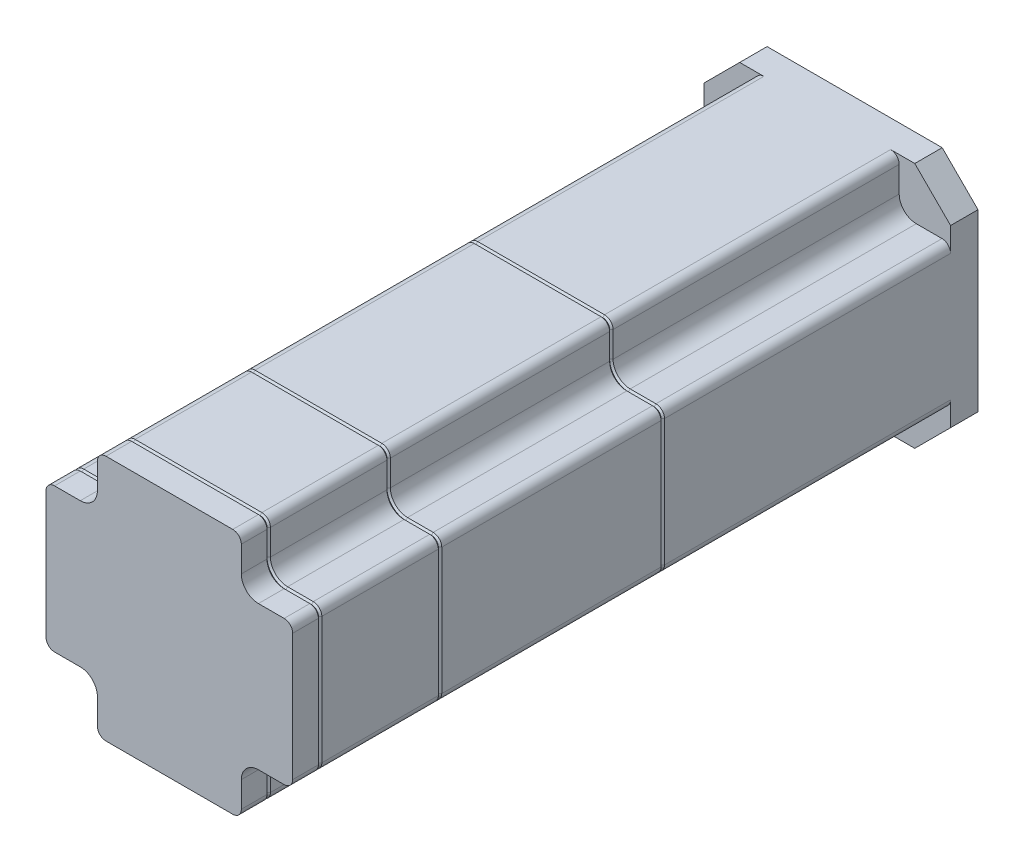
SolidWorks part; units mm, degrees
ref_plane "Front Plane" through (0, 0, 0) normal (0, 0, 1) x (1, 0, 0)
ref_plane "Top Plane" through (0, 0, 0) normal (0, 1, 0) x (1, 0, 0)
ref_plane "Right Plane" through (0, 0, 0) normal (1, 0, 0) x (0, 0, -1)
sketch "Sketch3" plane through (0, 0, 0) normal (0, 0, 1) x (1, 0, 0)
  line L1 (-36, -36) -> (36, -36)
  line L2 (-36, -36) -> (-36, 36)
  line L3 (-36, 36) -> (36, 36)
  line L4 (36, -36) -> (36, 36)
  line L5 (-36, -36) -> (36, 36) construction
  line L6 (-36, 36) -> (36, -36) construction
  point P0 (0, 0)
  dimension "D1" = 72
  dimension "D2" = 72
extrude "Boss-Extrude2" add sketch "Sketch3" along normal blind 8
chamfer "Chamfer1" distance 10.45 angle 45 4 edges at (36, -36, 4) (-36, -36, 4) (-36, 36, 4) (36, 36, 4)
sketch "Sketch5" plane through (0, 0, 8) normal (0, 0, 1) x (1, 0, 0)
  line L3 (-36, -21) -> (-26, -21)
  line L4 (-21, -36) -> (-21, -26)
  line L5 (-36, -36) -> (-21, -21) construction
  line L6 (-36, -21) -> (-21, -36) construction
  line L8 (-21, 36) -> (-21, 26)
  line L9 (-36, 21) -> (-26, 21)
  line L10 (36, 21) -> (26, 21)
  line L11 (21, 36) -> (21, 26)
  line L12 (21, -36) -> (21, -26)
  line L13 (36, -21) -> (26, -21)
  line L20 (-25.55, -36) -> (25.55, -36)
  line L21 (25.55, -36) -> (36, -25.55)
  line L22 (36, -25.55) -> (36, 25.55)
  line L23 (36, 25.55) -> (25.55, 36)
  line L24 (25.55, 36) -> (-25.55, 36)
  line L25 (-25.55, 36) -> (-36, 25.55)
  line L26 (-36, 25.55) -> (-36, -25.55)
  line L27 (-36, -25.55) -> (-25.55, -36)
  line L28 (-25.55, -36) -> (25.55, -36)
  line L29 (25.55, -36) -> (36, -25.55)
  line L30 (36, -25.55) -> (36, 25.55)
  line L31 (36, 25.55) -> (25.55, 36)
  line L32 (25.55, 36) -> (-25.55, 36)
  line L33 (-25.55, 36) -> (-36, 25.55)
  line L34 (-36, 25.55) -> (-36, -25.55)
  line L35 (-36, -25.55) -> (-25.55, -36)
  arc A0 (-26, -21) -> (-21, -26) centre (-26, -26) cw
  arc A1 (-21, 26) -> (-26, 21) centre (-26, 26) cw
  arc A2 (26, 21) -> (21, 26) centre (26, 26) cw
  arc A3 (21, -26) -> (26, -21) centre (26, -26) cw
  point P0 (-28.5, -28.5)
  point P30 (0, 0)
  line M12 (-25.55, -36) -> (25.55, -36)
  line M14 (36, -25.55) -> (36, 25.55)
  line M16 (25.55, 36) -> (-25.55, 36)
  line M18 (-36, 25.55) -> (-36, -25.55)
  dimension "D5" = 5
  dimension "D1" = 0
  dimension "D3" = 15
  dimension "D6" = 4
extrude "Boss-Extrude3" add sketch "Sketch5" along normal blind 192 contours L12 A3 L13 L10 A2 L11 L8 A1 L9 L3 A0 L4 M14 M16 M18 M12
fillet "Fillet1" radius 2.5 8 edges at (-36, -21, 104) (-21, -36, 104) (21, -36, 104) (36, -21, 104) (36, 21, 104) (21, 36, 104) (-21, 36, 104) (-36, 21, 104)
ref_plane "Plane1" through (0, 0, 192) normal (0, 0, 1) x (1, 0, 0)
sketch "Sketch8" plane through (0, 0, 192) normal (0, 0, 1) x (1, 0, 0)
  line L24 (-46, 18.5) -> (-46, -18.5)
  line L25 (-33.5, -31) -> (-31, -31)
  line L26 (-31, -31) -> (-31, -33.5)
  line L27 (-18.5, -46) -> (18.5, -46)
  line L28 (31, -33.5) -> (31, -31)
  line L29 (31, -31) -> (33.5, -31)
  line L30 (46, -18.5) -> (46, 18.5)
  line L31 (33.5, 31) -> (31, 31)
  line L32 (31, 31) -> (31, 33.5)
  line L33 (18.5, 46) -> (-18.5, 46)
  line L34 (-31, 33.5) -> (-31, 31)
  line L35 (-31, 31) -> (-33.5, 31)
  line L36 (-46, 18.5) -> (-46, -18.5)
  line L37 (-33.5, -31) -> (-31, -31)
  line L38 (-31, -31) -> (-31, -33.5)
  line L39 (-18.5, -46) -> (18.5, -46)
  line L40 (31, -33.5) -> (31, -31)
  line L41 (31, -31) -> (33.5, -31)
  line L42 (46, -18.5) -> (46, 18.5)
  line L43 (33.5, 31) -> (31, 31)
  line L44 (31, 31) -> (31, 33.5)
  line L45 (18.5, 46) -> (-18.5, 46)
  line L46 (-31, 33.5) -> (-31, 31)
  line L47 (-31, 31) -> (-33.5, 31)
  line L60 (-35.5, 18.5) -> (-35.5, -18.5)
  line L61 (-33.5, -20.5) -> (-26, -20.5)
  line L62 (-20.5, -26) -> (-20.5, -33.5)
  line L63 (-18.5, -35.5) -> (18.5, -35.5)
  line L64 (20.5, -33.5) -> (20.5, -26)
  line L65 (26, -20.5) -> (33.5, -20.5)
  line L66 (35.5, -18.5) -> (35.5, 18.5)
  line L67 (33.5, 20.5) -> (26, 20.5)
  line L68 (20.5, 26) -> (20.5, 33.5)
  line L69 (18.5, 35.5) -> (-18.5, 35.5)
  line L70 (-20.5, 33.5) -> (-20.5, 26)
  line L71 (-26, 20.5) -> (-33.5, 20.5)
  line L72 (-35.5, 18.5) -> (-35.5, -18.5)
  line L73 (-33.5, -20.5) -> (-26, -20.5)
  line L74 (-20.5, -26) -> (-20.5, -33.5)
  line L75 (-18.5, -35.5) -> (18.5, -35.5)
  line L76 (20.5, -33.5) -> (20.5, -26)
  line L77 (26, -20.5) -> (33.5, -20.5)
  line L78 (35.5, -18.5) -> (35.5, 18.5)
  line L79 (33.5, 20.5) -> (26, 20.5)
  line L80 (20.5, 26) -> (20.5, 33.5)
  line L81 (18.5, 35.5) -> (-18.5, 35.5)
  line L82 (-20.5, 33.5) -> (-20.5, 26)
  line L83 (-26, 20.5) -> (-33.5, 20.5)
  arc A24 (-46, -18.5) -> (-33.5, -31) centre (-33.5, -18.5) ccw
  arc A25 (-31, -33.5) -> (-18.5, -46) centre (-18.5, -33.5) ccw
  arc A26 (18.5, -46) -> (31, -33.5) centre (18.5, -33.5) ccw
  arc A27 (33.5, -31) -> (46, -18.5) centre (33.5, -18.5) ccw
  arc A28 (46, 18.5) -> (33.5, 31) centre (33.5, 18.5) ccw
  arc A29 (31, 33.5) -> (18.5, 46) centre (18.5, 33.5) ccw
  arc A30 (-18.5, 46) -> (-31, 33.5) centre (-18.5, 33.5) ccw
  arc A31 (-33.5, 31) -> (-46, 18.5) centre (-33.5, 18.5) ccw
  arc A32 (-46, -18.5) -> (-33.5, -31) centre (-33.5, -18.5) ccw
  arc A33 (-31, -33.5) -> (-18.5, -46) centre (-18.5, -33.5) ccw
  arc A34 (18.5, -46) -> (31, -33.5) centre (18.5, -33.5) ccw
  arc A35 (33.5, -31) -> (46, -18.5) centre (33.5, -18.5) ccw
  arc A36 (46, 18.5) -> (33.5, 31) centre (33.5, 18.5) ccw
  arc A37 (31, 33.5) -> (18.5, 46) centre (18.5, 33.5) ccw
  arc A38 (-18.5, 46) -> (-31, 33.5) centre (-18.5, 33.5) ccw
  arc A39 (-33.5, 31) -> (-46, 18.5) centre (-33.5, 18.5) ccw
  arc A52 (-35.5, -18.5) -> (-33.5, -20.5) centre (-33.5, -18.5) ccw
  arc A53 (-20.5, -26) -> (-26, -20.5) centre (-26, -26) ccw
  arc A54 (-20.5, -33.5) -> (-18.5, -35.5) centre (-18.5, -33.5) ccw
  arc A55 (18.5, -35.5) -> (20.5, -33.5) centre (18.5, -33.5) ccw
  arc A56 (26, -20.5) -> (20.5, -26) centre (26, -26) ccw
  arc A57 (33.5, -20.5) -> (35.5, -18.5) centre (33.5, -18.5) ccw
  arc A58 (35.5, 18.5) -> (33.5, 20.5) centre (33.5, 18.5) ccw
  arc A59 (20.5, 26) -> (26, 20.5) centre (26, 26) ccw
  arc A60 (20.5, 33.5) -> (18.5, 35.5) centre (18.5, 33.5) ccw
  arc A61 (-18.5, 35.5) -> (-20.5, 33.5) centre (-18.5, 33.5) ccw
  arc A62 (-26, 20.5) -> (-20.5, 26) centre (-26, 26) ccw
  arc A63 (-33.5, 20.5) -> (-35.5, 18.5) centre (-33.5, 18.5) ccw
  arc A64 (-35.5, -18.5) -> (-33.5, -20.5) centre (-33.5, -18.5) ccw
  arc A65 (-20.5, -26) -> (-26, -20.5) centre (-26, -26) ccw
  arc A66 (-20.5, -33.5) -> (-18.5, -35.5) centre (-18.5, -33.5) ccw
  arc A67 (18.5, -35.5) -> (20.5, -33.5) centre (18.5, -33.5) ccw
  arc A68 (26, -20.5) -> (20.5, -26) centre (26, -26) ccw
  arc A69 (33.5, -20.5) -> (35.5, -18.5) centre (33.5, -18.5) ccw
  arc A70 (35.5, 18.5) -> (33.5, 20.5) centre (33.5, 18.5) ccw
  arc A71 (20.5, 26) -> (26, 20.5) centre (26, 26) ccw
  arc A72 (20.5, 33.5) -> (18.5, 35.5) centre (18.5, 33.5) ccw
  arc A73 (-18.5, 35.5) -> (-20.5, 33.5) centre (-18.5, 33.5) ccw
  arc A74 (-26, 20.5) -> (-20.5, 26) centre (-26, 26) ccw
  arc A75 (-33.5, 20.5) -> (-35.5, 18.5) centre (-33.5, 18.5) ccw
  dimension "D1" = 10
  dimension "D2" = 0.5
extrude "Cut-Extrude2" cut sketch "Sketch8" against normal blind 0.5 draft 45 and the other way blind 0.5 draft 45
ref_plane "Plane2" through (0, 0, 157) normal (0, 0, 1) x (1, 0, 0)
sketch "Sketch9" plane through (0, 0, 157) normal (0, 0, 1) x (1, 0, 0)
  line L12 (31, -31) -> (33.5, -31)
  line L13 (31, -33.5) -> (31, -31)
  line L14 (-18.5, -46) -> (18.5, -46)
  line L15 (-31, -31) -> (-31, -33.5)
  line L16 (-33.5, -31) -> (-31, -31)
  line L17 (-46, 18.5) -> (-46, -18.5)
  line L18 (-31, 31) -> (-33.5, 31)
  line L19 (-31, 33.5) -> (-31, 31)
  line L20 (18.5, 46) -> (-18.5, 46)
  line L21 (31, 31) -> (31, 33.5)
  line L22 (33.5, 31) -> (31, 31)
  line L23 (46, -18.5) -> (46, 18.5)
  line L24 (31, -31) -> (33.5, -31)
  line L25 (31, -33.5) -> (31, -31)
  line L26 (-18.5, -46) -> (18.5, -46)
  line L27 (-31, -31) -> (-31, -33.5)
  line L28 (-33.5, -31) -> (-31, -31)
  line L29 (-46, 18.5) -> (-46, -18.5)
  line L30 (-31, 31) -> (-33.5, 31)
  line L31 (-31, 33.5) -> (-31, 31)
  line L32 (18.5, 46) -> (-18.5, 46)
  line L33 (31, 31) -> (31, 33.5)
  line L34 (33.5, 31) -> (31, 31)
  line L35 (46, -18.5) -> (46, 18.5)
  line L36 (20.5, 26) -> (20.5, 33.5)
  line L37 (18.5, 35.5) -> (-18.5, 35.5)
  line L38 (-20.5, 33.5) -> (-20.5, 26)
  line L39 (-26, 20.5) -> (-33.5, 20.5)
  line L40 (-35.5, 18.5) -> (-35.5, -18.5)
  line L41 (-33.5, -20.5) -> (-26, -20.5)
  line L42 (-20.5, -26) -> (-20.5, -33.5)
  line L43 (-18.5, -35.5) -> (18.5, -35.5)
  line L44 (20.5, -33.5) -> (20.5, -26)
  line L45 (26, -20.5) -> (33.5, -20.5)
  line L46 (35.5, -18.5) -> (35.5, 18.5)
  line L47 (33.5, 20.5) -> (26, 20.5)
  line L48 (20.5, 26) -> (20.5, 33.5)
  line L49 (18.5, 35.5) -> (-18.5, 35.5)
  line L50 (-20.5, 33.5) -> (-20.5, 26)
  line L51 (-26, 20.5) -> (-33.5, 20.5)
  line L52 (-35.5, 18.5) -> (-35.5, -18.5)
  line L53 (-33.5, -20.5) -> (-26, -20.5)
  line L54 (-20.5, -26) -> (-20.5, -33.5)
  line L55 (-18.5, -35.5) -> (18.5, -35.5)
  line L56 (20.5, -33.5) -> (20.5, -26)
  line L57 (26, -20.5) -> (33.5, -20.5)
  line L58 (35.5, -18.5) -> (35.5, 18.5)
  line L59 (33.5, 20.5) -> (26, 20.5)
  arc A8 (18.5, -46) -> (31, -33.5) centre (18.5, -33.5) ccw
  arc A9 (-31, -33.5) -> (-18.5, -46) centre (-18.5, -33.5) ccw
  arc A10 (-46, -18.5) -> (-33.5, -31) centre (-33.5, -18.5) ccw
  arc A11 (-33.5, 31) -> (-46, 18.5) centre (-33.5, 18.5) ccw
  arc A12 (-18.5, 46) -> (-31, 33.5) centre (-18.5, 33.5) ccw
  arc A13 (31, 33.5) -> (18.5, 46) centre (18.5, 33.5) ccw
  arc A14 (46, 18.5) -> (33.5, 31) centre (33.5, 18.5) ccw
  arc A15 (33.5, -31) -> (46, -18.5) centre (33.5, -18.5) ccw
  arc A16 (18.5, -46) -> (31, -33.5) centre (18.5, -33.5) ccw
  arc A17 (-31, -33.5) -> (-18.5, -46) centre (-18.5, -33.5) ccw
  arc A18 (-46, -18.5) -> (-33.5, -31) centre (-33.5, -18.5) ccw
  arc A19 (-33.5, 31) -> (-46, 18.5) centre (-33.5, 18.5) ccw
  arc A20 (-18.5, 46) -> (-31, 33.5) centre (-18.5, 33.5) ccw
  arc A21 (31, 33.5) -> (18.5, 46) centre (18.5, 33.5) ccw
  arc A22 (46, 18.5) -> (33.5, 31) centre (33.5, 18.5) ccw
  arc A23 (33.5, -31) -> (46, -18.5) centre (33.5, -18.5) ccw
  arc A28 (20.5, 33.5) -> (18.5, 35.5) centre (18.5, 33.5) ccw
  arc A29 (-18.5, 35.5) -> (-20.5, 33.5) centre (-18.5, 33.5) ccw
  arc A30 (-26, 20.5) -> (-20.5, 26) centre (-26, 26) ccw
  arc A31 (-33.5, 20.5) -> (-35.5, 18.5) centre (-33.5, 18.5) ccw
  arc A32 (-35.5, -18.5) -> (-33.5, -20.5) centre (-33.5, -18.5) ccw
  arc A33 (-20.5, -26) -> (-26, -20.5) centre (-26, -26) ccw
  arc A34 (-20.5, -33.5) -> (-18.5, -35.5) centre (-18.5, -33.5) ccw
  arc A35 (18.5, -35.5) -> (20.5, -33.5) centre (18.5, -33.5) ccw
  arc A36 (26, -20.5) -> (20.5, -26) centre (26, -26) ccw
  arc A37 (33.5, -20.5) -> (35.5, -18.5) centre (33.5, -18.5) ccw
  arc A38 (35.5, 18.5) -> (33.5, 20.5) centre (33.5, 18.5) ccw
  arc A39 (20.5, 26) -> (26, 20.5) centre (26, 26) ccw
  arc A40 (20.5, 33.5) -> (18.5, 35.5) centre (18.5, 33.5) ccw
  arc A41 (-18.5, 35.5) -> (-20.5, 33.5) centre (-18.5, 33.5) ccw
  arc A42 (-26, 20.5) -> (-20.5, 26) centre (-26, 26) ccw
  arc A43 (-33.5, 20.5) -> (-35.5, 18.5) centre (-33.5, 18.5) ccw
  arc A44 (-35.5, -18.5) -> (-33.5, -20.5) centre (-33.5, -18.5) ccw
  arc A45 (-20.5, -26) -> (-26, -20.5) centre (-26, -26) ccw
  arc A46 (-20.5, -33.5) -> (-18.5, -35.5) centre (-18.5, -33.5) ccw
  arc A47 (18.5, -35.5) -> (20.5, -33.5) centre (18.5, -33.5) ccw
  arc A48 (26, -20.5) -> (20.5, -26) centre (26, -26) ccw
  arc A49 (33.5, -20.5) -> (35.5, -18.5) centre (33.5, -18.5) ccw
  arc A50 (35.5, 18.5) -> (33.5, 20.5) centre (33.5, 18.5) ccw
  arc A51 (20.5, 26) -> (26, 20.5) centre (26, 26) ccw
  dimension "D1" = 0
  dimension "D2" = 0
extrude "Cut-Extrude3" cut sketch "Sketch9" against normal blind 0.5 draft 45 and the other way blind 0.5 draft 45
ref_plane "Plane3" through (0, 0, 92) normal (0, 0, 1) x (1, 0, 0)
sketch "Sketch10" plane through (0, 0, 92) normal (0, 0, 1) x (1, 0, 0)
  line L12 (18.5, 46) -> (-18.5, 46)
  line L13 (31, 31) -> (31, 33.5)
  line L14 (33.5, 31) -> (31, 31)
  line L15 (46, -18.5) -> (46, 18.5)
  line L16 (31, -31) -> (33.5, -31)
  line L17 (31, -33.5) -> (31, -31)
  line L18 (-18.5, -46) -> (18.5, -46)
  line L19 (-31, -31) -> (-31, -33.5)
  line L20 (-33.5, -31) -> (-31, -31)
  line L21 (-46, 18.5) -> (-46, -18.5)
  line L22 (-31, 31) -> (-33.5, 31)
  line L23 (-31, 33.5) -> (-31, 31)
  line L24 (18.5, 46) -> (-18.5, 46)
  line L25 (31, 31) -> (31, 33.5)
  line L26 (33.5, 31) -> (31, 31)
  line L27 (46, -18.5) -> (46, 18.5)
  line L28 (31, -31) -> (33.5, -31)
  line L29 (31, -33.5) -> (31, -31)
  line L30 (-18.5, -46) -> (18.5, -46)
  line L31 (-31, -31) -> (-31, -33.5)
  line L32 (-33.5, -31) -> (-31, -31)
  line L33 (-46, 18.5) -> (-46, -18.5)
  line L34 (-31, 31) -> (-33.5, 31)
  line L35 (-31, 33.5) -> (-31, 31)
  line L36 (-18.5, -35.5) -> (18.5, -35.5)
  line L37 (-20.5, -26) -> (-20.5, -33.5)
  line L38 (-33.5, -20.5) -> (-26, -20.5)
  line L39 (-35.5, 18.5) -> (-35.5, -18.5)
  line L40 (-26, 20.5) -> (-33.5, 20.5)
  line L41 (-20.5, 33.5) -> (-20.5, 26)
  line L42 (18.5, 35.5) -> (-18.5, 35.5)
  line L43 (20.5, 26) -> (20.5, 33.5)
  line L44 (33.5, 20.5) -> (26, 20.5)
  line L45 (35.5, -18.5) -> (35.5, 18.5)
  line L46 (26, -20.5) -> (33.5, -20.5)
  line L47 (20.5, -33.5) -> (20.5, -26)
  line L48 (-18.5, -35.5) -> (18.5, -35.5)
  line L49 (-20.5, -26) -> (-20.5, -33.5)
  line L50 (-33.5, -20.5) -> (-26, -20.5)
  line L51 (-35.5, 18.5) -> (-35.5, -18.5)
  line L52 (-26, 20.5) -> (-33.5, 20.5)
  line L53 (-20.5, 33.5) -> (-20.5, 26)
  line L54 (18.5, 35.5) -> (-18.5, 35.5)
  line L55 (20.5, 26) -> (20.5, 33.5)
  line L56 (33.5, 20.5) -> (26, 20.5)
  line L57 (35.5, -18.5) -> (35.5, 18.5)
  line L58 (26, -20.5) -> (33.5, -20.5)
  line L59 (20.5, -33.5) -> (20.5, -26)
  arc A8 (-18.5, 46) -> (-31, 33.5) centre (-18.5, 33.5) ccw
  arc A9 (31, 33.5) -> (18.5, 46) centre (18.5, 33.5) ccw
  arc A10 (46, 18.5) -> (33.5, 31) centre (33.5, 18.5) ccw
  arc A11 (33.5, -31) -> (46, -18.5) centre (33.5, -18.5) ccw
  arc A12 (18.5, -46) -> (31, -33.5) centre (18.5, -33.5) ccw
  arc A13 (-31, -33.5) -> (-18.5, -46) centre (-18.5, -33.5) ccw
  arc A14 (-46, -18.5) -> (-33.5, -31) centre (-33.5, -18.5) ccw
  arc A15 (-33.5, 31) -> (-46, 18.5) centre (-33.5, 18.5) ccw
  arc A16 (-18.5, 46) -> (-31, 33.5) centre (-18.5, 33.5) ccw
  arc A17 (31, 33.5) -> (18.5, 46) centre (18.5, 33.5) ccw
  arc A18 (46, 18.5) -> (33.5, 31) centre (33.5, 18.5) ccw
  arc A19 (33.5, -31) -> (46, -18.5) centre (33.5, -18.5) ccw
  arc A20 (18.5, -46) -> (31, -33.5) centre (18.5, -33.5) ccw
  arc A21 (-31, -33.5) -> (-18.5, -46) centre (-18.5, -33.5) ccw
  arc A22 (-46, -18.5) -> (-33.5, -31) centre (-33.5, -18.5) ccw
  arc A23 (-33.5, 31) -> (-46, 18.5) centre (-33.5, 18.5) ccw
  arc A28 (18.5, -35.5) -> (20.5, -33.5) centre (18.5, -33.5) ccw
  arc A29 (-20.5, -33.5) -> (-18.5, -35.5) centre (-18.5, -33.5) ccw
  arc A30 (-20.5, -26) -> (-26, -20.5) centre (-26, -26) ccw
  arc A31 (-35.5, -18.5) -> (-33.5, -20.5) centre (-33.5, -18.5) ccw
  arc A32 (-33.5, 20.5) -> (-35.5, 18.5) centre (-33.5, 18.5) ccw
  arc A33 (-26, 20.5) -> (-20.5, 26) centre (-26, 26) ccw
  arc A34 (-18.5, 35.5) -> (-20.5, 33.5) centre (-18.5, 33.5) ccw
  arc A35 (20.5, 33.5) -> (18.5, 35.5) centre (18.5, 33.5) ccw
  arc A36 (20.5, 26) -> (26, 20.5) centre (26, 26) ccw
  arc A37 (35.5, 18.5) -> (33.5, 20.5) centre (33.5, 18.5) ccw
  arc A38 (33.5, -20.5) -> (35.5, -18.5) centre (33.5, -18.5) ccw
  arc A39 (26, -20.5) -> (20.5, -26) centre (26, -26) ccw
  arc A40 (18.5, -35.5) -> (20.5, -33.5) centre (18.5, -33.5) ccw
  arc A41 (-20.5, -33.5) -> (-18.5, -35.5) centre (-18.5, -33.5) ccw
  arc A42 (-20.5, -26) -> (-26, -20.5) centre (-26, -26) ccw
  arc A43 (-35.5, -18.5) -> (-33.5, -20.5) centre (-33.5, -18.5) ccw
  arc A44 (-33.5, 20.5) -> (-35.5, 18.5) centre (-33.5, 18.5) ccw
  arc A45 (-26, 20.5) -> (-20.5, 26) centre (-26, 26) ccw
  arc A46 (-18.5, 35.5) -> (-20.5, 33.5) centre (-18.5, 33.5) ccw
  arc A47 (20.5, 33.5) -> (18.5, 35.5) centre (18.5, 33.5) ccw
  arc A48 (20.5, 26) -> (26, 20.5) centre (26, 26) ccw
  arc A49 (35.5, 18.5) -> (33.5, 20.5) centre (33.5, 18.5) ccw
  arc A50 (33.5, -20.5) -> (35.5, -18.5) centre (33.5, -18.5) ccw
  arc A51 (26, -20.5) -> (20.5, -26) centre (26, -26) ccw
  dimension "D1" = 0
  dimension "D2" = 0
extrude "Cut-Extrude4" cut sketch "Sketch10" against normal blind 0.5 draft 45 and the other way blind 0.5 draft 45
